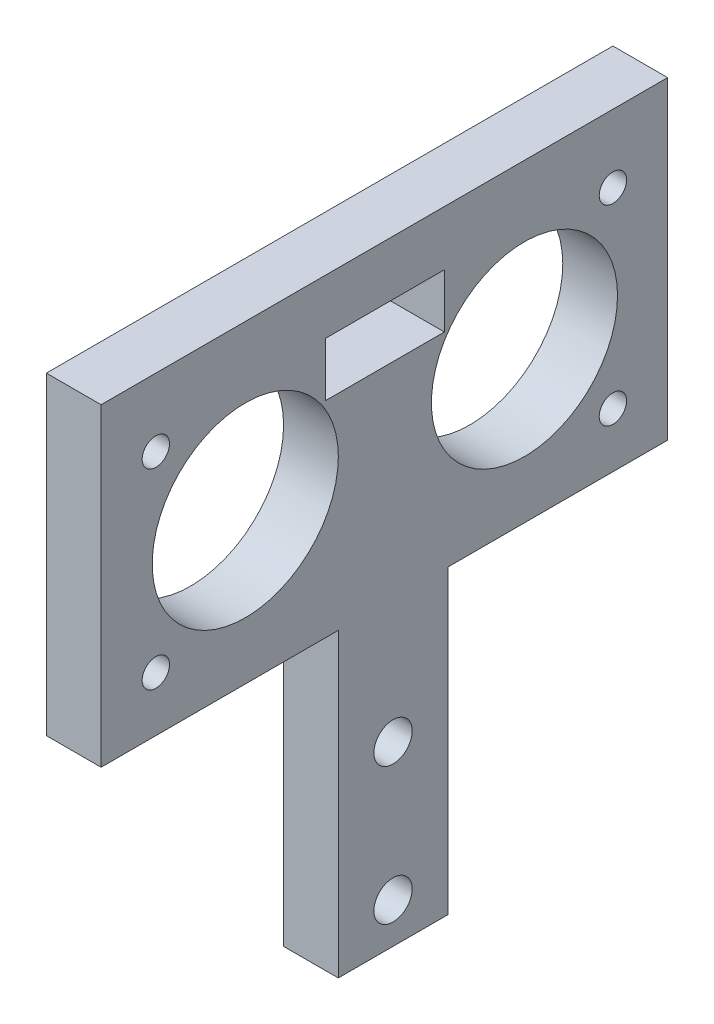
SolidWorks part; units mm, degrees
ref_plane "Front Plane" through (0, 0, 0) normal (0, 0, 1) x (1, 0, 0)
ref_plane "Top Plane" through (0, 0, 0) normal (0, 1, 0) x (1, 0, 0)
ref_plane "Right Plane" through (0, 0, 0) normal (1, 0, 0) x (0, 0, -1)
sketch "Sketch1" plane through (0, 0, 0) normal (1, 0, 0) x (0, 0, -1)
  line L0 (62.997, -55.8297) -> (88.397, -55.8297)
  line L2 (-64.003, 27.8375) -> (-64.003, -55.8297)
  line L4 (62.997, 27.8375) -> (62.997, -55.8297)
  line L6 (-89.403, -65.9897) -> (-89.403, -55.8297)
  line L7 (-89.403, -55.8297) -> (-64.003, -55.8297)
  line L8 (88.397, -65.9897) -> (88.397, -55.8297)
  line L9 (-89.403, -65.9897) -> (88.397, -65.9897)
  line L10 (-64.003, -13.9961) -> (75.8155, -13.9961) construction
  line L16 (-64.003, 27.8375) -> (62.997, 27.8375)
extrude "Boss-Extrude1" add sketch "Sketch1" along normal blind 5.08
sketch "Sketch2" plane through (0, 0, 0) normal (1, 0, 0) x (0, 0, -1)
  line L6 (-89.403, -65.9897) -> (88.397, -65.9897) construction
  line L7 (50.297, -65.9897) -> (-51.303, -65.9897)
  line L8 (50.297, -65.9897) -> (50.297, -55.8297)
  line L9 (50.297, -55.8297) -> (-51.303, -55.8297)
  line L10 (-51.303, -65.9897) -> (-51.303, -55.8297)
  line L11 (62.997, -55.8297) -> (62.997, 27.8375) construction
  line L12 (-64.003, 27.8375) -> (-64.003, -55.8297) construction
  dimension "D1" = 12.7
  dimension "D2" = 12.7
extrude "Cut-Extrude3" cut sketch "Sketch2" along normal blind 22.86
sketch "Sketch8" plane through (0, 0, 0) normal (1, 0, 0) x (0, 0, -1)
  line L0 (62.997, -55.8297) -> (62.997, 27.8375) construction
  circle A0 centre (12.197, -10.1006) radius 8.636
  circle A1 centre (-13.711, -10.1006) radius 8.636
  dimension "D1" = 17.272
  dimension "D2" = 50.8
  dimension "D3" = 25.908
  dimension "D4" = 10.1006
sketch "Sketch9" plane through (0, 0, 0) normal (1, 0, 0) x (0, 0, -1)
  line L0 (-23.458, -10.1006) -> (24.1858, -10.1006) construction
  line L1 (-23.458, 0.1544) -> (-23.458, -20.3556) construction
  line L2 (-0.803, 0.1544) -> (-0.803, -23.8564) construction
  line L3 (21.852, 0.1544) -> (-23.458, 0.1544) construction
  circle A0 centre (-22.0102, -1.2239) radius 1.27
  circle A1 centre (-22.0102, -18.9772) radius 1.27
  circle A2 centre (20.4042, -18.9772) radius 1.27
  circle A3 centre (20.4042, -1.2239) radius 1.27
  dimension "D2" = 2.54
  dimension "D1" = 1.4478
  dimension "D3" = 1.2239
sketch "Sketch13" plane through (0, 0, 0) normal (1, 0, 0) x (0, 0, -1)
  line L0 (21.852, 0.1544) -> (-23.458, 0.1544) construction
  line L1 (-6.2582, 0) -> (4.7654, 0)
  line L2 (-6.2582, 0) -> (-6.2582, -5.0038)
  line L3 (-6.2582, -5.0038) -> (4.7654, -5.0038)
  line L4 (4.7654, 0) -> (4.7654, -5.0038)
  dimension "D1" = 5.0038
  dimension "D2" = 0.1544
  dimension "D3" = 11.0236
  dimension "D4" = 6.2582
extrude "Cut-Extrude4" cut sketch "Sketch9" along normal blind 25.908
extrude "Cut-Extrude5" cut sketch "Sketch13" along normal blind 25.908
extrude "Cut-Extrude6" cut sketch "Sketch8" along normal blind 25.908
sketch "Sketch14" plane through (0, 0, 0) normal (1, 0, 0) x (0, 0, -1)
  line L1 (-27.0902, 5.08) -> (25.4842, 5.08)
  line L2 (-27.0902, 5.08) -> (-27.0902, -24.0572)
  line L3 (-27.0902, -24.0572) -> (25.4842, -24.0572)
  line L4 (25.4842, 5.08) -> (25.4842, -24.0572)
  line L5 (-111.6829, 44.5623) -> (100.5201, 44.5623)
  line L6 (-111.6829, 44.5623) -> (-111.6829, -77.9583)
  line L7 (-111.6829, -77.9583) -> (100.5201, -77.9583)
  line L8 (100.5201, 44.5623) -> (100.5201, -77.9583)
  circle A0 centre (-22.0102, -18.9772) radius 1.27 construction
  circle A1 centre (20.4042, -18.9772) radius 1.27 construction
  dimension "D2" = 5.08
  dimension "D3" = 5.08
  dimension "D4" = 5.08
  dimension "D1" = 5.08
extrude "Cut-Extrude7" cut sketch "Sketch14" along normal blind 25.908
sketch "Sketch15" plane through (0, 0, 0) normal (1, 0, 0) x (0, 0, -1)
  line L0 (-27.0902, -66.04) -> (-27.0902, -22.3178)
  line L2 (-27.0902, -66.04) -> (25.4842, -66.04)
  line L3 (25.4842, -66.04) -> (25.4842, -22.3178)
  line L4 (-27.0902, -24.0572) -> (-27.0902, 5.08) construction
  line L5 (-27.0902, -22.3178) -> (25.4842, -22.3178)
  dimension "D1" = 66.04
  dimension "D2" = 25.4842
  dimension "D3" = 22.3178
extrude "Boss-Extrude2" add sketch "Sketch15" along normal blind 5.08
sketch "Sketch17" plane through (0, 0, 0) normal (1, 0, 0) x (0, 0, -1)
  line L0 (0, 0) -> (0, -71.7288) construction
  line L1 (-30.6594, -24.0572) -> (-5.08, -24.0572)
  line L2 (-30.6594, -24.0572) -> (-30.6594, -60.96)
  line L3 (-30.6594, -60.96) -> (-5.08, -60.96)
  line L4 (-5.08, -24.0572) -> (-5.08, -60.96)
  line L5 (-27.0902, -66.04) -> (25.4842, -66.04) construction
  line L6 (30.6594, -24.0572) -> (5.08, -24.0572)
  line L7 (30.6594, -24.0572) -> (30.6594, -60.96)
  line L8 (30.6594, -60.96) -> (5.08, -60.96)
  line L9 (5.08, -24.0572) -> (5.08, -60.96)
  circle A0 centre (-22.0102, -18.9772) radius 1.27 construction
  dimension "D1" = 5.08
  dimension "D2" = 5.08
  dimension "D3" = 5.08
  dimension "D4" = 30.6594
extrude "Cut-Extrude8" cut sketch "Sketch17" along normal blind 10.16
ref_plane "Plane1" through (0, -66.04, 0) normal (0, 1, 0) x (1, 0, 0)
sketch "Sketch18" plane through (0, -66.04, 0) normal (0, 1, 0) x (1, 0, 0)
  line L0 (5.08, -27.0902) -> (0, -27.0902) construction
  line L1 (5.08, -27.0902) -> (5.08, 25.4842) construction
  line L2 (0, -0.803) -> (20.3338, -0.803) construction
  line L3 (0, -27.0902) -> (0, 25.4842) construction
  circle A0 centre (0, -22.0102) radius 1.7526
  circle A1 centre (0, 20.4042) radius 1.7526
  dimension "D1" = 3.5052
  dimension "D2" = 5.08
  dimension "D3" = 5.08
extrude "Cut-Extrude9" cut sketch "Sketch18" along normal blind 10.16
sketch "Sketch19" plane through (0, 0, 0) normal (1, 0, 0) x (0, 0, -1)
  line L1 (-40.4731, -51.9972) -> (37.5141, -51.9972)
  line L2 (-40.4731, -51.9972) -> (-40.4731, -68.3665)
  line L3 (-40.4731, -68.3665) -> (37.5141, -68.3665)
  line L4 (37.5141, -51.9972) -> (37.5141, -68.3665)
  dimension "D1" = 27.94
  dimension "D2" = 37.5141
  dimension "D3" = 40.4731
  dimension "D4" = 68.3665
extrude "Cut-Extrude10" cut sketch "Sketch19" along normal blind 19.05
sketch "Sketch20" plane through (0, 0, 0) normal (1, 0, 0) x (0, 0, -1)
  circle A1 centre (0, -48.26) radius 1.778
  circle A2 centre (0, -35.56) radius 1.778
  dimension "D3" = 12.7
  dimension "D2" = 35.56
  dimension "D1" = 3.556
extrude "Cut-Extrude11" cut sketch "Sketch20" along normal blind 19.05
